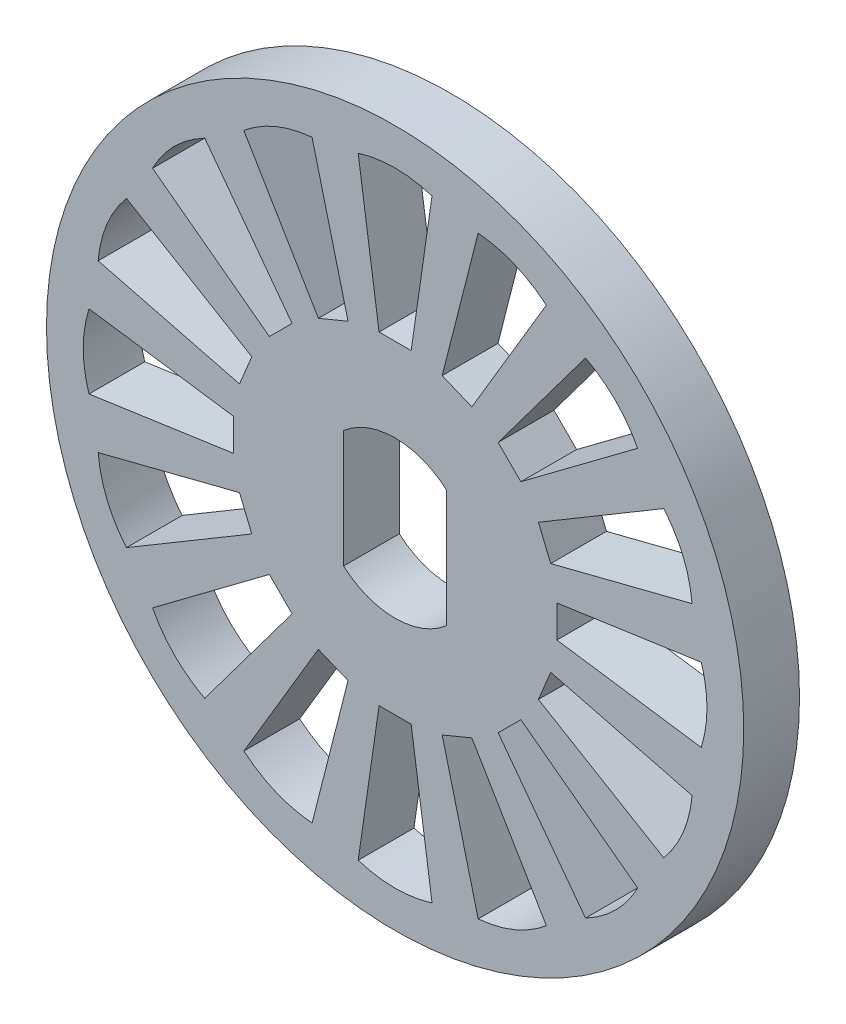
SolidWorks part; units mm, degrees
ref_plane "Front Plane" through (0, 0, 0) normal (0, 0, 1) x (1, 0, 0)
ref_plane "Top Plane" through (0, 0, 0) normal (0, 1, 0) x (1, 0, 0)
ref_plane "Right Plane" through (0, 0, 0) normal (1, 0, 0) x (0, 0, -1)
sketch "Sketch1" plane through (0, 0, 0) normal (0, 0, 1) x (1, 0, 0)
  line L0 (0, 29.3396) -> (0, -28.4316) construction
  line L1 (-34.5346, 0) -> (35.2675, 0) construction
  circle A0 centre (0, 0) radius 12.5
  dimension "D1" = 25
extrude "Boss-Extrude1" add sketch "Sketch1" along normal blind 2
sketch "Sketch2" plane through (0, 0, 2) normal (0, 0, 1) x (1, 0, 0)
  line L0 (0, 12.0457) -> (0, -12.3213) construction
  line L1 (-16.0712, 0) -> (16.7447, 0) construction
  line L2 (1.85, 2.1018) -> (1.85, -2.1018)
  line L3 (-1.85, 2.1018) -> (-1.85, -2.1018)
  arc A0 (-1.85, -2.1018) -> (1.85, -2.1018) centre (0, 0) ccw
  arc A1 (1.85, 2.1018) -> (-1.85, 2.1018) centre (0, 0) ccw
  point P11 (0, 0)
  dimension "D1" = 3.7
  dimension "D2" = 5.6
extrude "Cut-Extrude1" cut sketch "Sketch2" against normal blind 2
sketch "Sketch3" plane through (0, 0, 2) normal (0, 0, 1) x (1, 0, 0)
  line L0 (0, 12.1988) -> (0, -12.3825) construction
  line L1 (-14.8773, 0) -> (14.2345, 0) construction
  line L2 (-0.5755, 5.8) -> (0.5755, 5.8)
  line L3 (0.5755, 5.8) -> (1.3234, 10.9753)
  line L4 (-0.5755, 5.8) -> (-1.3234, 10.9753)
  line L6 (2.7513, 5.1383) -> (5.4227, 9.6334)
  line L7 (1.6878, 5.5788) -> (2.7513, 5.1383)
  line L8 (1.6878, 5.5788) -> (2.9774, 10.6463)
  line L9 (4.5082, 3.6943) -> (8.6965, 6.8249)
  line L10 (3.6943, 4.5082) -> (4.5082, 3.6943)
  line L11 (3.6943, 4.5082) -> (6.8249, 8.6965)
  line L12 (5.5788, 1.6878) -> (10.6463, 2.9774)
  line L13 (5.1383, 2.7513) -> (5.5788, 1.6878)
  line L14 (5.1383, 2.7513) -> (9.6334, 5.4227)
  line L15 (5.8, -0.5755) -> (10.9753, -1.3234)
  line L16 (5.8, 0.5755) -> (5.8, -0.5755)
  line L17 (5.8, 0.5755) -> (10.9753, 1.3234)
  line L18 (5.1383, -2.7513) -> (9.6334, -5.4227)
  line L19 (5.5788, -1.6878) -> (5.1383, -2.7513)
  line L20 (5.5788, -1.6878) -> (10.6463, -2.9774)
  line L21 (3.6943, -4.5082) -> (6.8249, -8.6965)
  line L22 (4.5082, -3.6943) -> (3.6943, -4.5082)
  line L23 (4.5082, -3.6943) -> (8.6965, -6.8249)
  line L24 (1.6878, -5.5788) -> (2.9774, -10.6463)
  line L25 (2.7513, -5.1383) -> (1.6878, -5.5788)
  line L26 (2.7513, -5.1383) -> (5.4227, -9.6334)
  line L27 (-0.5755, -5.8) -> (-1.3234, -10.9753)
  line L28 (0.5755, -5.8) -> (-0.5755, -5.8)
  line L29 (0.5755, -5.8) -> (1.3234, -10.9753)
  line L30 (-2.7513, -5.1383) -> (-5.4227, -9.6334)
  line L31 (-1.6878, -5.5788) -> (-2.7513, -5.1383)
  line L32 (-1.6878, -5.5788) -> (-2.9774, -10.6463)
  line L33 (-4.5082, -3.6943) -> (-8.6965, -6.8249)
  line L34 (-3.6943, -4.5082) -> (-4.5082, -3.6943)
  line L35 (-3.6943, -4.5082) -> (-6.8249, -8.6965)
  line L36 (-5.5788, -1.6878) -> (-10.6463, -2.9774)
  line L37 (-5.1383, -2.7513) -> (-5.5788, -1.6878)
  line L38 (-5.1383, -2.7513) -> (-9.6334, -5.4227)
  line L39 (-5.8, 0.5755) -> (-10.9753, 1.3234)
  line L40 (-5.8, -0.5755) -> (-5.8, 0.5755)
  line L41 (-5.8, -0.5755) -> (-10.9753, -1.3234)
  line L42 (-5.1383, 2.7513) -> (-9.6334, 5.4227)
  line L43 (-5.5788, 1.6878) -> (-5.1383, 2.7513)
  line L44 (-5.5788, 1.6878) -> (-10.6463, 2.9774)
  line L45 (-3.6943, 4.5082) -> (-6.8249, 8.6965)
  line L46 (-4.5082, 3.6943) -> (-3.6943, 4.5082)
  line L47 (-4.5082, 3.6943) -> (-8.6965, 6.8249)
  line L48 (-1.6878, 5.5788) -> (-2.9774, 10.6463)
  line L49 (-2.7513, 5.1383) -> (-1.6878, 5.5788)
  line L50 (-2.7513, 5.1383) -> (-5.4227, 9.6334)
  arc A2 (1.85, 2.1018) -> (-1.85, 2.1018) centre (0, 0) ccw construction
  spline S0 degree 2 poles (-1.3234, 10.9753) (0, 11.3884) (1.3234, 10.9753) knots 0 0 0 1 1 1
  spline S1 degree 2 poles (2.9774, 10.6463) (4.3581, 10.5215) (5.4227, 9.6334) knots 0 0 0 1 1 1
  spline S2 degree 2 poles (6.8249, 8.6965) (8.0528, 8.0528) (8.6965, 6.8249) knots 0 0 0 1 1 1
  spline S3 degree 2 poles (9.6334, 5.4227) (10.5215, 4.3581) (10.6463, 2.9774) knots 0 0 0 1 1 1
  spline S4 degree 2 poles (10.9753, 1.3234) (11.3884, 0) (10.9753, -1.3234) knots 0 0 0 1 1 1
  spline S5 degree 2 poles (10.6463, -2.9774) (10.5215, -4.3581) (9.6334, -5.4227) knots 0 0 0 1 1 1
  spline S6 degree 2 poles (8.6965, -6.8249) (8.0528, -8.0528) (6.8249, -8.6965) knots 0 0 0 1 1 1
  spline S7 degree 2 poles (5.4227, -9.6334) (4.3581, -10.5215) (2.9774, -10.6463) knots 0 0 0 1 1 1
  spline S8 degree 2 poles (1.3234, -10.9753) (0, -11.3884) (-1.3234, -10.9753) knots 0 0 0 1 1 1
  spline S9 degree 2 poles (-2.9774, -10.6463) (-4.3581, -10.5215) (-5.4227, -9.6334) knots 0 0 0 1 1 1
  spline S10 degree 2 poles (-6.8249, -8.6965) (-8.0528, -8.0528) (-8.6965, -6.8249) knots 0 0 0 1 1 1
  spline S11 degree 2 poles (-9.6334, -5.4227) (-10.5215, -4.3581) (-10.6463, -2.9774) knots 0 0 0 1 1 1
  spline S12 degree 2 poles (-10.9753, -1.3234) (-11.3884, 0) (-10.9753, 1.3234) knots 0 0 0 1 1 1
  spline S13 degree 2 poles (-10.6463, 2.9774) (-10.5215, 4.3581) (-9.6334, 5.4227) knots 0 0 0 1 1 1
  spline S14 degree 2 poles (-8.6965, 6.8249) (-8.0528, 8.0528) (-6.8249, 8.6965) knots 0 0 0 1 1 1
  spline S15 degree 2 poles (-5.4227, 9.6334) (-4.3581, 10.5215) (-2.9774, 10.6463) knots 0 0 0 1 1 1
  point P5 (0, 0)
  point P10 (-0.6826, 5.7)
  point P18 (-0.5755, 5.7)
  point P91 (0, 0)
  point P121 (0, 0)
  dimension "D2" = 3
  dimension "D1" = 16
extrude "Cut-Extrude2" cut sketch "Sketch3" against normal blind 2
